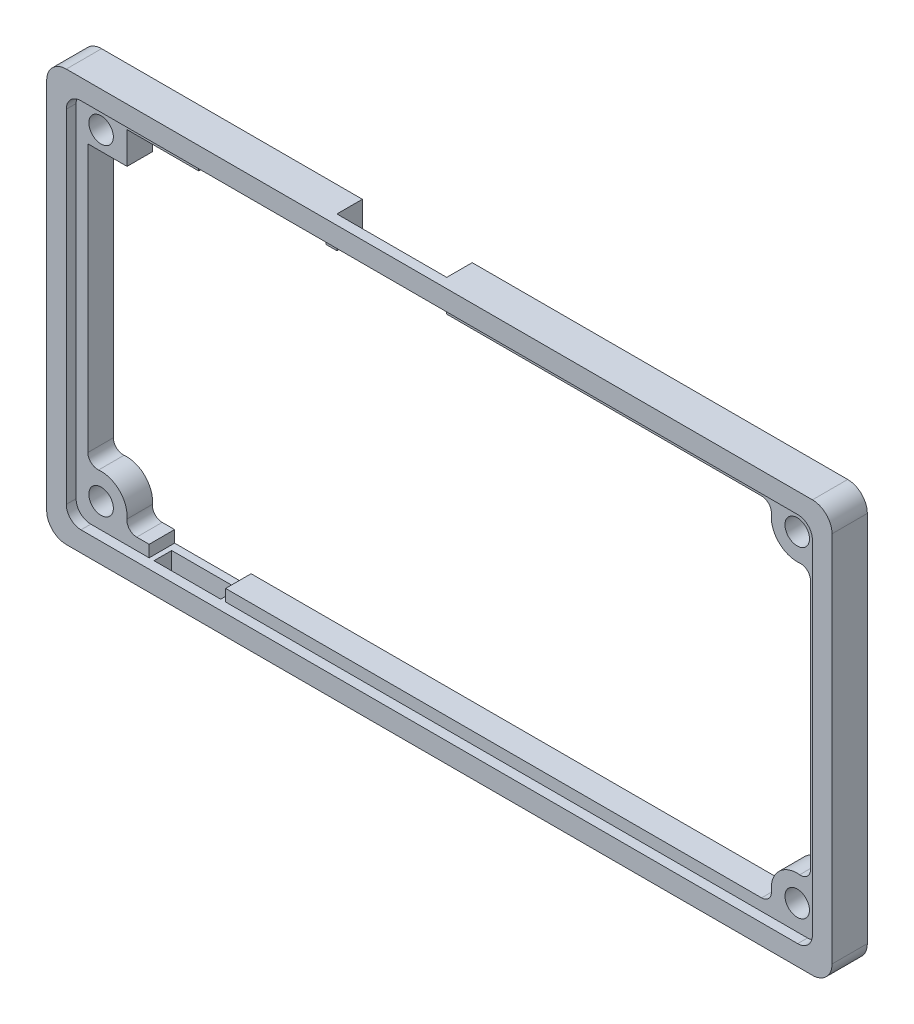
SolidWorks part; units mm, degrees
ref_plane "Front Plane" through (0, 0, 0) normal (0, 0, 1) x (1, 0, 0)
ref_plane "Top Plane" through (0, 0, 0) normal (0, 1, 0) x (1, 0, 0)
ref_plane "Right Plane" through (0, 0, 0) normal (1, 0, 0) x (0, 0, -1)
sketch "Sketch1" plane through (0, 0, 0) normal (0, 0, 1) x (1, 0, 0)
  line L0 (-36, 19) -> (-36, -19) construction
  line L1 (-36, -21) -> (44.1, -21)
  line L2 (-36, -21) -> (-36, 21)
  line L3 (-36, 21) -> (44.1, 21)
  line L4 (44.1, -21) -> (44.1, 21)
  line L5 (42.1, -21) -> (-34, -21) construction
  line L6 (44.1, 19) -> (44.1, -19) construction
  line L7 (-34, 21) -> (42.1, 21) construction
  line L8 (35.9168, -17.75) -> (-27.8168, -17.75)
  line L9 (40.9, -12.7668) -> (40.9, 12.7668)
  line L10 (40.5, -18.75) -> (-18.75, -18.75) construction
  line L11 (41.9, 17.35) -> (41.9, -17.35) construction
  line L12 (4.05, -21) -> (4.05, 21) construction
  line L13 (44.1, 0) -> (4.05, 0) construction
  line L15 (-32.8, -12.7668) -> (-32.8, 14.5)
  line L16 (35.9168, 17.75) -> (-27.8168, 17.75)
  line L17 (-32.8, 14.5) -> (-28.8, 14.5)
  line L18 (-28.8, 14.5) -> (-28.8, 17.75)
  line L19 (-32.3, 14.5) -> (-24.3, 14.5) construction
  line L21 (-28.8, 17.75) -> (-27.8168, 17.75)
  line L22 (-33.8, -17.35) -> (-33.8, 17.35) construction
  circle A0 centre (39.55, -16.4) radius 1.25
  circle A1 centre (-31.45, -16.4) radius 1.25
  arc A2 (-31.7041, -13.7622) -> (-32.8, -12.7668) centre (-31.8, -12.7668) cw
  arc A3 (-28.8122, -16.6541) -> (-31.7041, -13.7622) centre (-31.45, -16.4) ccw
  circle A4 centre (39.55, -16.4) radius 1.25 construction
  arc A8 (36.9122, -16.6541) -> (39.8041, -13.7622) centre (39.55, -16.4) cw
  arc A9 (39.8041, -13.7622) -> (40.9, -12.7668) centre (39.9, -12.7668) ccw
  arc A10 (36.9122, -16.6541) -> (35.9168, -17.75) centre (35.9168, -16.75) cw
  arc A11 (-28.8122, -16.6541) -> (-27.8168, -17.75) centre (-27.8168, -16.75) ccw
  circle A12 centre (39.55, 16.4) radius 1.25
  arc A13 (36.9122, 16.6541) -> (35.9168, 17.75) centre (35.9168, 16.75) ccw
  arc A14 (36.9122, 16.6541) -> (39.8041, 13.7622) centre (39.55, 16.4) ccw
  arc A15 (39.8041, 13.7622) -> (40.9, 12.7668) centre (39.9, 12.7668) cw
  circle A16 centre (-31.45, 16.4) radius 1.25
  circle A17 centre (-31.45, 16.4) radius 1.25 construction
  point P28 (4.05, -17.75)
  point P53 (40.9, 0)
  dimension "D3" = 2.65
  dimension "D4" = 1
  dimension "D5" = 1
  dimension "D1" = 1
  dimension "D2" = 1
  dimension "D6" = 5
extrude "Boss-Extrude1" add sketch "Sketch1" along normal blind 2.6
sketch "Sketch2" plane through (0, 0, 2.6) normal (0, 0, 1) x (1, 0, 0)
  line L0 (40.5, -18.75) -> (-18.75, -18.75) construction
  line L1 (44.1, -21) -> (-36, -21)
  line L2 (44.1, -21) -> (44.1, 21)
  line L3 (44.1, 21) -> (-36, 21)
  line L4 (-36, -21) -> (-36, 21)
  line L5 (-34, 18.95) -> (42.1, 18.95)
  line L6 (-34, 18.95) -> (-34, -18.95)
  line L7 (-34, -18.95) -> (42.1, -18.95)
  line L8 (42.1, 18.95) -> (42.1, -18.95)
  line L9 (41.9, 17.35) -> (41.9, -17.35) construction
  line L10 (-33.8, -17.35) -> (-33.8, 17.35) construction
  line L11 (-32.4, 18.75) -> (-21.5, 18.75) construction
  dimension "D1" = 0.2
  dimension "D2" = 0.2
  dimension "D3" = 0.2
  dimension "D4" = 0.2
extrude "Boss-Extrude2" add sketch "Sketch2" along normal blind 1
fillet "Fillet1" radius 2 4 edges at (44.1, 21, 1.8) (44.1, -21, 1.8) (-36, -21, 1.8) (-36, 21, 1.8)
fillet "Fillet2" radius 1.5 4 edges at (42.1, 18.95, 3.1) (-34, 18.95, 3.1) (-34, -18.95, 3.1) (42.1, -18.95, 3.1)
sketch "Sketch3" plane through (0, 0, 2.6) normal (0, 0, 1) x (1, 0, 0)
  line L0 (40.6, 18.95) -> (-32.5, 18.95) construction
  line L1 (-8.5, 13.1) -> (-21.5, 13.1)
  line L2 (-8.5, 13.1) -> (-8.5, 18.95)
  line L3 (-8.5, 18.95) -> (-21.5, 18.95)
  line L4 (-21.5, 13.1) -> (-21.5, 18.95)
  line L5 (-21.5, 13.1) -> (-21.5, 18.75) construction
extrude "Cut-Extrude1" cut sketch "Sketch3" against normal through all
sketch "Sketch4" plane through (0, 0, 2.6) normal (0, 0, 1) x (1, 0, 0)
  line L0 (-18.75, -18.75) -> (-18.75, -13.55) construction
  line L1 (-18.75, -17.75) -> (-26.55, -17.75)
  line L2 (-18.75, -17.75) -> (-18.75, -18.95)
  line L3 (-18.75, -18.95) -> (-26.55, -18.95)
  line L4 (-26.55, -17.75) -> (-26.55, -18.95)
  line L5 (-32.5, -18.95) -> (40.6, -18.95) construction
  line L6 (-26.55, -13.55) -> (-26.55, -18.75) construction
  line L7 (-27.8168, -17.75) -> (35.9168, -17.75) construction
extrude "Cut-Extrude2" cut sketch "Sketch4" against normal through all
sketch "Sketch5" plane through (0, -21, 0) normal (0, -1, 0) x (1, 0, 0)
  line L0 (-34, 3.6) -> (42.1, 3.6) construction
  line L1 (-26.05, 2.6) -> (-19.25, 2.6)
  line L2 (-26.05, 2.6) -> (-26.05, 0.8)
  line L3 (-26.05, 0.8) -> (-19.25, 0.8)
  line L4 (-19.25, 2.6) -> (-19.25, 0.8)
  line L5 (-26.55, 0) -> (-26.55, 2.6) construction
  line L6 (-18.75, 0) -> (-18.75, 2.6) construction
  dimension "D1" = 1
  dimension "D2" = 0.5
  dimension "D3" = 0.5
  dimension "D4" = 1.8
extrude "Cut-USB" cut sketch "Sketch5" against normal blind 4
sketch "Sketch6" plane through (0, 0, 0) normal (0, 0, -1) x (-1, 0, 0)
  line L0 (-42.1, 21) -> (34, 21) construction
  line L1 (7.4, 21) -> (-3.8, 21)
  line L2 (7.4, 21) -> (7.4, 17.75)
  line L3 (7.4, 17.75) -> (-3.8, 17.75)
  line L4 (-3.8, 21) -> (-3.8, 17.75)
  line L5 (-35.9168, 17.75) -> (8.5, 17.75) construction
  line L7 (-3.6, 20.85) -> (-3.6, 10.85) construction
  line L8 (7.2, 10.85) -> (7.2, 20.85) construction
  point P8 (0, 0)
  dimension "D1" = 0.2
  dimension "D2" = 0.2
extrude "Cut-Pill" cut sketch "Sketch6" against normal up to surface (2.6 mm away) up to face at (38.3, 16.4, 2.6)
